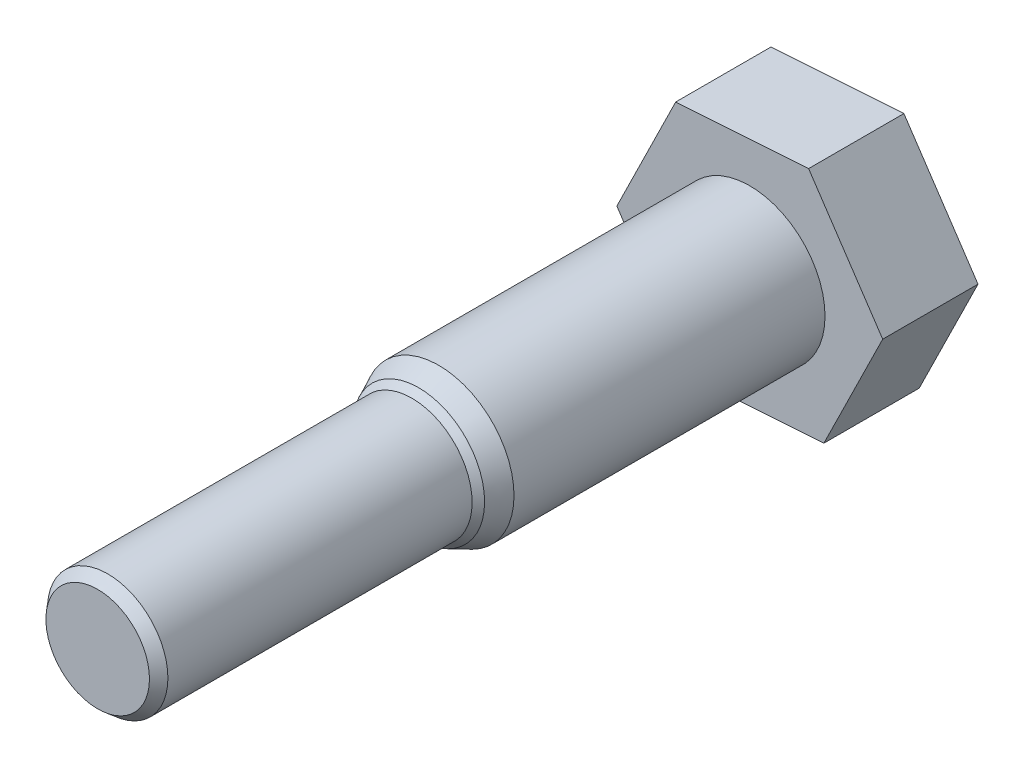
SolidWorks part; units mm, degrees
ref_plane "前视基准面" through (0, 0, 0) normal (0, 0, 1) x (1, 0, 0)
ref_plane "上视基准面" through (0, 0, 0) normal (0, 1, 0) x (1, 0, 0)
ref_plane "右视基准面" through (0, 0, 0) normal (1, 0, 0) x (0, 0, -1)
sketch "草图1" plane through (0, 0, 0) normal (0, 0, 1) x (1, 0, 0)
  circle A0 centre (0, 0) radius 15
  dimension "D1" = 30
extrude "拉伸1" add sketch "草图1" along normal blind 1
sketch "草图2" plane through (0, 0, 0) normal (0, 0, 1) x (1, 0, 0)
  line L1 (14.7707, -22.0717) -> (26.5, 1.7559)
  line L2 (26.5, 1.7559) -> (11.7293, 23.8276)
  line L3 (11.7293, 23.8276) -> (-14.7707, 22.0717)
  line L4 (-14.7707, 22.0717) -> (-26.5, -1.7559)
  line L5 (-26.5, -1.7559) -> (-11.7293, -23.8276)
  line L6 (-11.7293, -23.8276) -> (14.7707, -22.0717)
  circle A0 centre (0, 0) radius 23 construction
  dimension "D1" = 46
  dimension "D2" = 53
extrude "拉伸2" add sketch "草图2" along normal blind 19
sketch "草图9" plane through (0, 0, 19) normal (0, 0, 1) x (1, 0, 0)
  circle A0 centre (0, 0) radius 15
  dimension "D1" = 30
extrude "拉伸3" add sketch "草图9" along normal blind 62
sketch "草图11" plane through (0, 0, 81) normal (0, 0, 1) x (1, 0, 0)
  circle A0 centre (0, 0) radius 15
  dimension "D1" = 30
extrude "拉伸6" add sketch "草图11" along normal blind 4 draft 25
sketch "草图12" plane through (0, 0, 85) normal (0, 0, 1) x (1, 0, 0)
  circle A0 centre (0, 0) radius 12
  dimension "D1" = 24
extrude "拉伸7" add sketch "草图12" along normal blind 62
sketch "草图13" plane through (0, 0, 85) normal (0, 0, 1) x (1, 0, 0)
  circle A0 centre (0, 0) radius 13.1348
  dimension "D1" = 26.2695
extrude "拉伸8" add sketch "草图13" along normal blind 2 draft 40
sketch "草图15" plane through (0, 0, 147) normal (0, 0, 1) x (1, 0, 0)
  circle A0 centre (0, 0) radius 12
  dimension "D1" = 24
extrude "拉伸9" add sketch "草图15" along normal blind 2 draft 40
